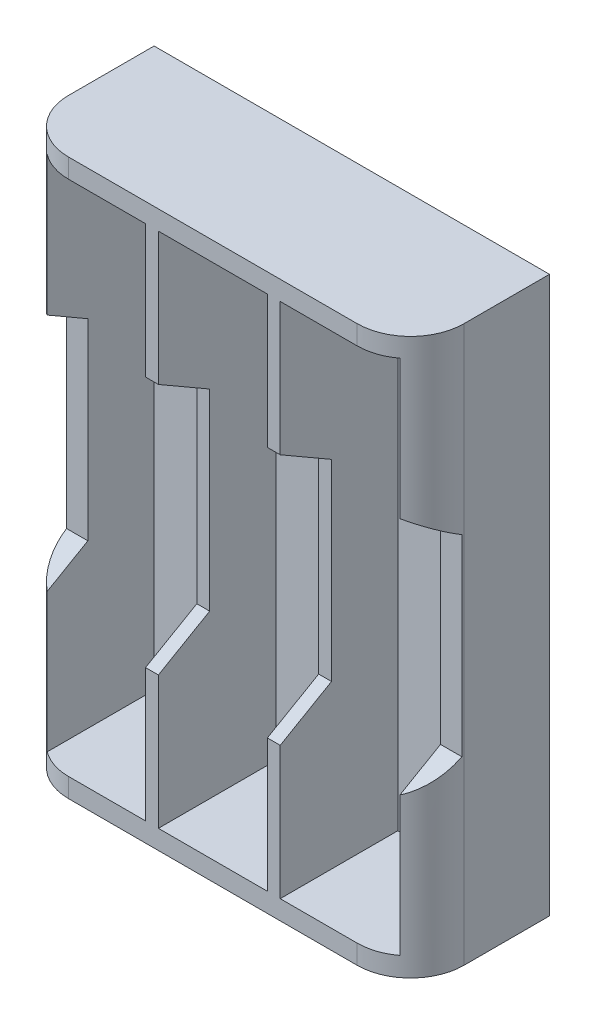
SolidWorks part; units mm, degrees
ref_plane "Front" through (0, 0, 0) normal (0, 0, 1) x (1, 0, 0)
ref_plane "Top" through (0, 0, 0) normal (0, 1, 0) x (1, 0, 0)
ref_plane "Right" through (0, 0, 0) normal (1, 0, 0) x (0, 0, -1)
sketch "Sketch1" plane through (0, 0, 0) normal (0, 0, 1) x (1, 0, 0)
  line L1 (-18.5, -26) -> (18.5, -26)
  line L2 (-18.5, -26) -> (-18.5, 26)
  line L3 (-18.5, 26) -> (18.5, 26)
  line L4 (18.5, -26) -> (18.5, 26)
  line L5 (-18.5, -26) -> (18.5, 26) construction
  line L6 (-18.5, 26) -> (18.5, -26) construction
  point P0 (0, 0)
  dimension "D1" = 52
  dimension "D2" = 37
extrude "Boss-Extrude1" add sketch "Sketch1" along normal blind 2
sketch "Sketch2" plane through (0, -26, 0) normal (0, -1, 0) x (1, 0, 0)
  line L0 (-13.5, 13) -> (13.5, 13)
  line L1 (0, 0) -> (0, 13) construction
  line L2 (-18.5, 0) -> (18.5, 0) construction
  line L3 (-18.5, 2) -> (-18.5, 8)
  line L4 (-18.5, 2) -> (18.5, 2)
  line L5 (-18.5, 2) -> (18.5, 2) construction
  line L6 (18.5, 2) -> (18.5, 8)
  arc A0 (-18.5, 8) -> (-13.5, 13) centre (-13.5, 8) cw
  arc A1 (18.5, 8) -> (13.5, 13) centre (13.5, 8) ccw
  point P17 (0, 2)
  dimension "D1" = 13
  dimension "D2" = 8
extrude "Boss-Extrude2" add sketch "Sketch2" against normal up to surface (52 mm away) up to face at (0, 26, 1)
sketch "Sketch3" plane through (0, 0, 13) normal (0, 0, 1) x (1, 0, 0)
  line L0 (-13.5, 26) -> (13.5, 26) construction
  line L1 (-5.1, 24.2) -> (5.1, 24.2)
  line L2 (-5.1, 24.2) -> (-5.1, -24.2)
  line L3 (-5.1, -24.2) -> (5.1, -24.2)
  line L4 (5.1, 24.2) -> (5.1, -24.2)
  line L5 (-5.1, 24.2) -> (5.1, -24.2) construction
  line L6 (-5.1, -24.2) -> (5.1, 24.2) construction
  line L7 (5.7, 26) -> (5.7, -26) construction
  line L8 (13.5, -26) -> (-13.5, -26) construction
  line L9 (16.5, 24.2) -> (16.5, -24.2)
  line L10 (16.5, -24.2) -> (6.3, -24.2)
  line L11 (6.3, 24.2) -> (6.3, -24.2)
  line L12 (16.5, 24.2) -> (6.3, 24.2)
  line L13 (0, 0) -> (0, -26) construction
  line L14 (-6.3, 24.2) -> (-6.3, -24.2)
  line L15 (-16.5, -24.2) -> (-6.3, -24.2)
  line L16 (-16.5, 24.2) -> (-16.5, -24.2)
  line L17 (-16.5, 24.2) -> (-6.3, 24.2)
  point P0 (0, 0)
  dimension "D1" = 10.2
  dimension "D2" = 1.8
  dimension "D3" = 0.6
extrude "Cut-Extrude1" cut sketch "Sketch3" against normal offset from surface (11 mm away) 2 up to face at (0, 0, 0)
sketch "Sketch4" plane through (0, 0, 0) normal (1, 0, 0) x (0, 0, -1)
  line L0 (0, 0) -> (-18, 0) construction
  line L1 (-18, -14.658) -> (-18, 14.658)
  line L2 (-18, 14.658) -> (-8.2, 9)
  line L3 (-8.2, 9) -> (-8.2, -9)
  line L4 (-18, -14.658) -> (-8.2, -9)
  line L5 (0, -26) -> (0, 26) construction
  line L6 (-13, 26) -> (-13, 24.2) construction
  point P7 (-8.2, 0)
  dimension "D1" = 8.2
  dimension "D2" = 18
  dimension "D3" = 60
  dimension "D4" = 5
extrude "Cut-Extrude2" cut sketch "Sketch4" against normal through all both and the other way through all
